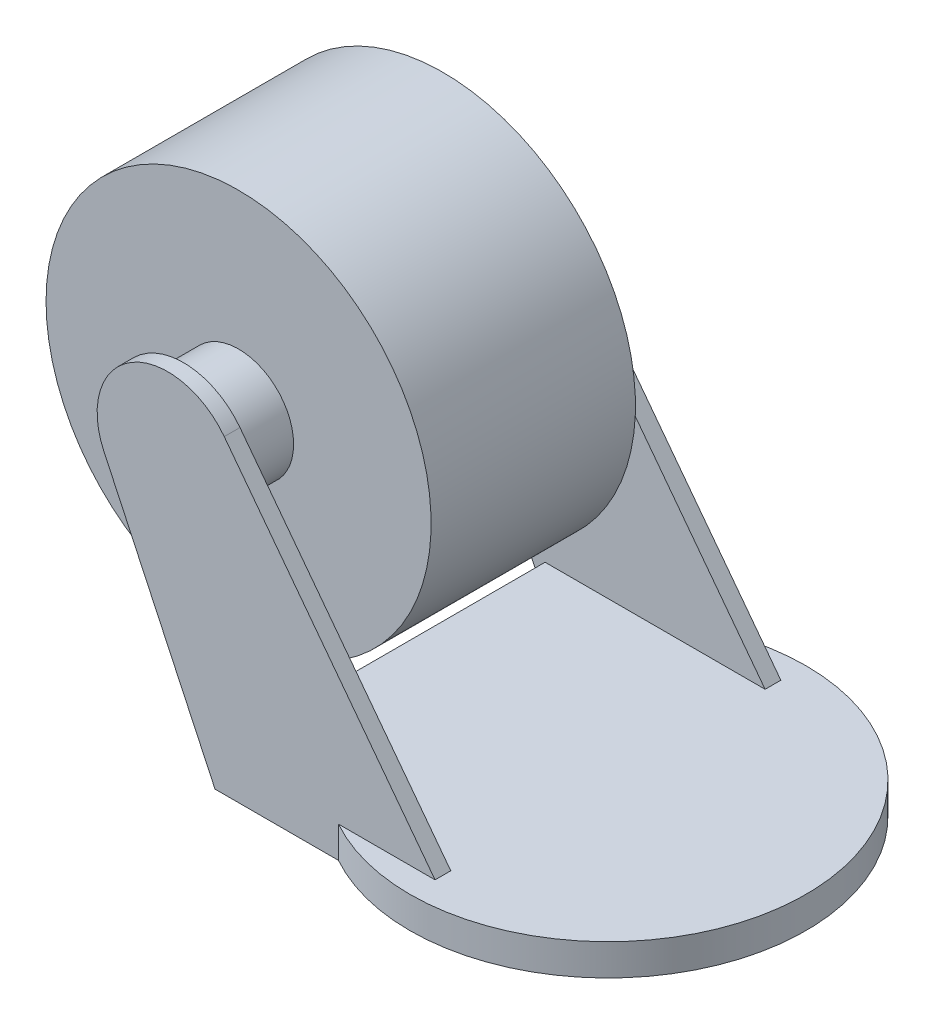
SolidWorks part; units mm, degrees
ref_plane "Front Plane" through (0, 0, 0) normal (0, 0, 1) x (1, 0, 0)
ref_plane "Top Plane" through (0, 0, 0) normal (0, 1, 0) x (1, 0, 0)
ref_plane "Right Plane" through (0, 0, 0) normal (1, 0, 0) x (0, 0, -1)
sketch "Sketch1" plane through (0, 0, 0) normal (0, 1, 0) x (1, 0, 0)
  line L1 (-14, 10) -> (-7.6655, 10)
  line L2 (-14, 10) -> (-14, -10)
  line L3 (-14, -10) -> (-7.6655, -10)
  arc A0 (-7.6655, -10) -> (-7.6655, 10) centre (0, 0) ccw
  dimension "D1" = 25.2
  dimension "D2" = 14
  dimension "D3" = 20
  dimension "D4" = 10
extrude "Boss-Extrude1" add sketch "Sketch1" along normal blind 2
sketch "Sketch2" plane through (0, 0, 10) normal (0, 0, 1) x (1, 0, 0)
  line L0 (0, 2) -> (-13.4122, 19.7162)
  line L3 (0, 2) -> (0, 0)
  line L4 (0, 0) -> (-14, 0)
  line L5 (-14, 0) -> (-21.0745, 15.0898)
  arc A0 (-13.4122, 19.7162) -> (-21.0745, 15.0898) centre (-17, 17) ccw
  dimension "D1" = 17
  dimension "D2" = 17
  dimension "D3" = 9
extrude "Boss-Extrude2" add sketch "Sketch2" along normal blind 1
sketch "Sketch3" plane through (0, 0, 11) normal (0, 0, 1) x (1, 0, 0)
  circle A0 centre (-17, 17) radius 3.5
  dimension "D1" = 7
extrude "Boss-Extrude4" add sketch "Sketch3" against normal up to surface (11 mm away) up to plane "Front Plane"
mirror "Mirror1" about plane through (0, 0, 0) normal (0, 0, 1) of "Boss-Extrude2", "Boss-Extrude4"
sketch "Sketch4" plane through (0, 0, 0) normal (0, 0, 1) x (1, 0, 0)
  circle A0 centre (-17, 17) radius 12.25
  dimension "D1" = 24.5
extrude "Boss-Extrude5" add sketch "Sketch4" along normal mid plane 13
